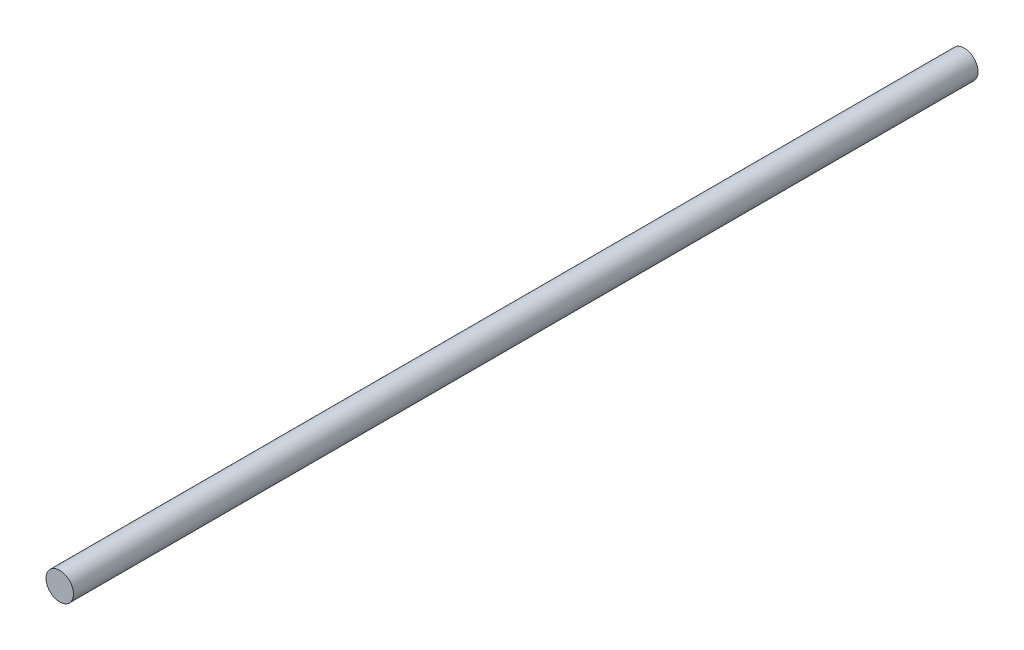
SolidWorks part; units mm, degrees
ref_plane "Front Plane" through (0, 0, 0) normal (0, 0, 1) x (1, 0, 0)
ref_plane "Top Plane" through (0, 0, 0) normal (0, 1, 0) x (1, 0, 0)
ref_plane "Right Plane" through (0, 0, 0) normal (1, 0, 0) x (0, 0, -1)
sketch "Sketch1" plane through (0, 0, 0) normal (0, 0, 1) x (1, 0, 0)
  circle A0 centre (0, 0) radius 2.5
  dimension "D1" = 5
extrude "Boss-Extrude1" add sketch "Sketch1" along normal blind 164.7
